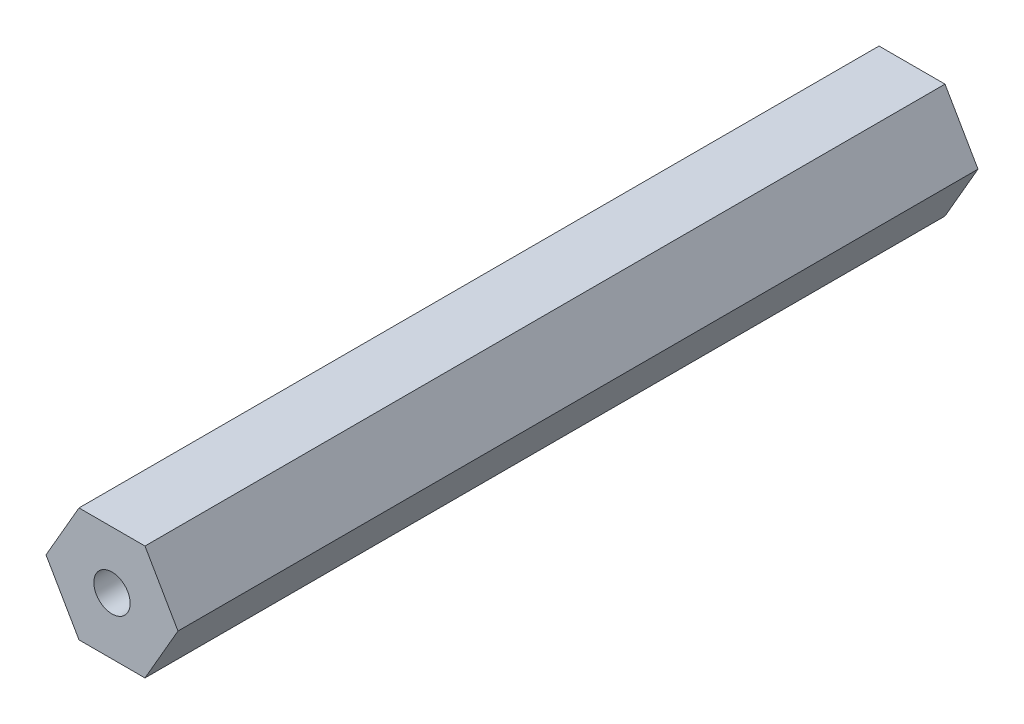
SolidWorks part; units mm, degrees
material "6061-T6 (SS)"
ref_plane "Front Plane" through (0, 0, 0) normal (0, 0, 1) x (1, 0, 0)
ref_plane "Top Plane" through (0, 0, 0) normal (0, 1, 0) x (1, 0, 0)
ref_plane "Right Plane" through (0, 0, 0) normal (1, 0, 0) x (0, 0, -1)
sketch "Sketch1" plane through (0, 0, 0) normal (0, 0, 1) x (1, 0, 0)
  line L1 (7.3323, 0) -> (3.6662, 6.35)
  line L2 (3.6662, 6.35) -> (-3.6662, 6.35)
  line L3 (-3.6662, 6.35) -> (-7.3323, 0)
  line L4 (-7.3323, 0) -> (-3.6662, -6.35)
  line L5 (-3.6662, -6.35) -> (3.6662, -6.35)
  line L6 (3.6662, -6.35) -> (7.3323, 0)
  circle A0 centre (0, 0) radius 4.1275 construction
  circle A1 centre (0, 0) radius 6.35 construction
  dimension "D1" = 8.255
  dimension "D2" = 12.7
extrude "Boss-Extrude1" add sketch "Sketch1" along normal mid plane 88.9
hole_wizard "#10-32 Tapped Hole1" positions "3DSketch1" profile "Sketch2" tap size "#10-32" standard "ANSI Inch"
sketch3d "3DSketch1"
  point P0 (0, 0, 44.45)
  point P4 (0, 0, -44.45)
  point P5 (0, 0, 0)
  point P6 (0, 0, 0)
sketch "Sketch2" plane through (0, 0, 44.45) normal (1, 0, 0) x (0, -1, 0)
  line L0 (0, 0) -> (0, 13.1513)
  line L1 (0, 13.1513) -> (2.0193, 11.938)
  line L2 (2.0193, 11.938) -> (2.0193, 0)
  line L5 (2.0193, 0) -> (0, 0)
  line L10 (0, 13.1513) -> (-2.0193, 11.938) construction
  line L11 (0, -6.35) -> (0, 107.95) construction
  dimension "Tap Drill Dia." = 4.0386
  dimension "Tap Drill Depth" = 11.938
  dimension "Drill Angle" = 118
cosmetic thread "Hole Thread1" parameters "D1"=9.652, "D2"=4.826
cosmetic thread "Hole Thread2" parameters "D1"=9.652, "D2"=4.826
